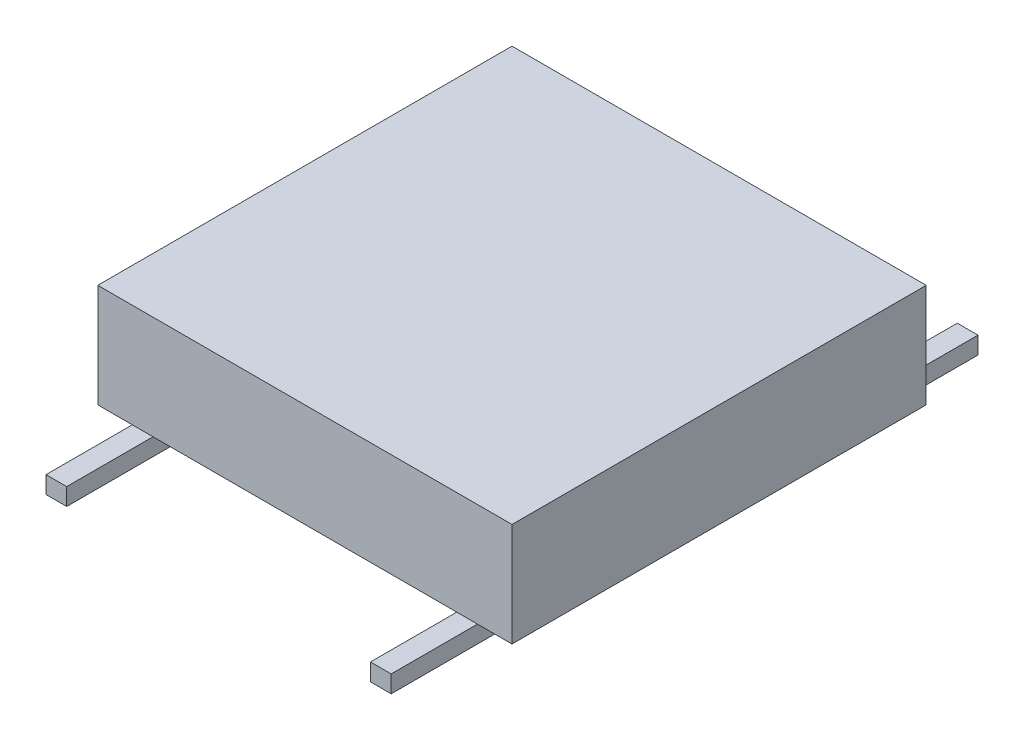
SolidWorks part; units mm, degrees
ref_plane "Front Plane" through (0, 0, 0) normal (0, 0, 1) x (1, 0, 0)
ref_plane "Top Plane" through (0, 0, 0) normal (0, 1, 0) x (1, 0, 0)
ref_plane "Right Plane" through (0, 0, 0) normal (1, 0, 0) x (0, 0, -1)
sketch "Sketch1" plane through (0, 0, 0) normal (0, 1, 0) x (1, 0, 0)
  line L1 (6, -6) -> (-6, -6)
  line L2 (6, -6) -> (6, 6)
  line L3 (6, 6) -> (-6, 6)
  line L4 (-6, -6) -> (-6, 6)
  line L5 (6, -6) -> (-6, 6) construction
  line L6 (6, 6) -> (-6, -6) construction
  point P0 (0, 0)
  dimension "D1" = 12
  dimension "D2" = 12
extrude "Boss-Extrude1" add sketch "Sketch1" along normal blind 3
sketch "Sketch2" plane through (0, 0, 6) normal (0, 0, 1) x (1, 0, 0)
  line L1 (6, 3) -> (6, 0) construction
  line L2 (4.4, 0) -> (5, 0)
  line L3 (4.4, 0) -> (4.4, -0.5)
  line L4 (4.4, -0.5) -> (5, -0.5)
  line L6 (5, 0) -> (5, -0.5)
  line L7 (-6, 3) -> (-6, 0) construction
  line L12 (-6, 0) -> (6, 0) construction
  line L13 (-5, 0) -> (-4.4, 0)
  line L14 (-5, 0) -> (-5, -0.5)
  line L15 (-5, -0.5) -> (-4.4, -0.5)
  line L16 (-4.4, 0) -> (-4.4, -0.5)
  dimension "D1" = 1
  dimension "D2" = 1
  dimension "D3" = 0.6
  dimension "D4" = 0.5
  dimension "D5" = 0.5
  dimension "D6" = 0.6
extrude "Boss-Extrude2" add sketch "Sketch2" along normal mid plane 5
mirror "Mirror1" about plane through (0, 0, 0) normal (0, 0, 1) of "Boss-Extrude2"
